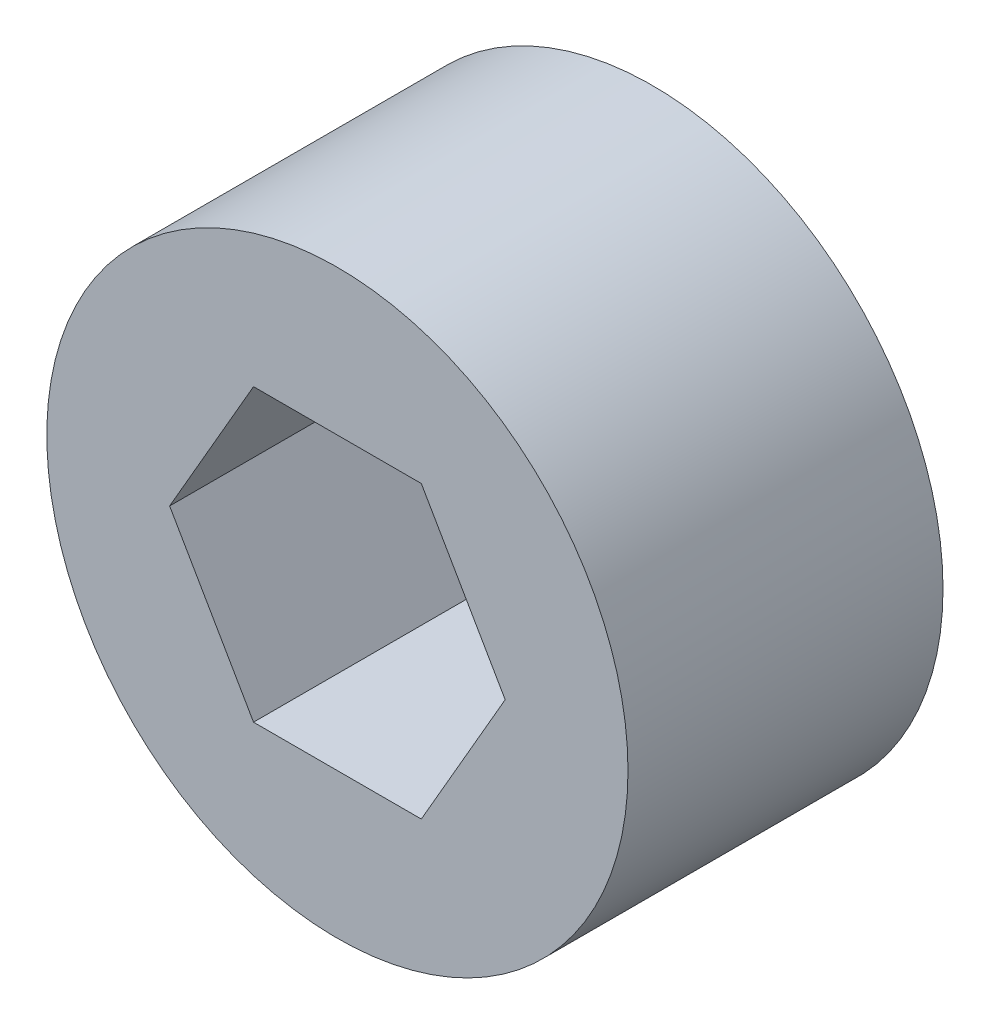
SolidWorks part; units mm, degrees
ref_plane "Front Plane" through (0, 0, 0) normal (0, 0, 1) x (1, 0, 0)
ref_plane "Top Plane" through (0, 0, 0) normal (0, 1, 0) x (1, 0, 0)
ref_plane "Right Plane" through (0, 0, 0) normal (1, 0, 0) x (0, 0, -1)
sketch "Sketch1" plane through (0, 0, 0) normal (0, 0, 1) x (1, 0, 0)
  line L1 (-7.3323, 0) -> (-3.6662, -6.35)
  line L2 (-3.6662, -6.35) -> (3.6662, -6.35)
  line L3 (3.6662, -6.35) -> (7.3323, 0)
  line L4 (7.3323, 0) -> (3.6662, 6.35)
  line L5 (3.6662, 6.35) -> (-3.6662, 6.35)
  line L6 (-3.6662, 6.35) -> (-7.3323, 0)
  circle A0 centre (0, 0) radius 6.35 construction
  circle A1 centre (0, 0) radius 12.7
  dimension "D2" = 25.4
  dimension "D1" = 12.7
extrude "Boss-Extrude1" add sketch "Sketch1" along normal mid plane 13.7668
